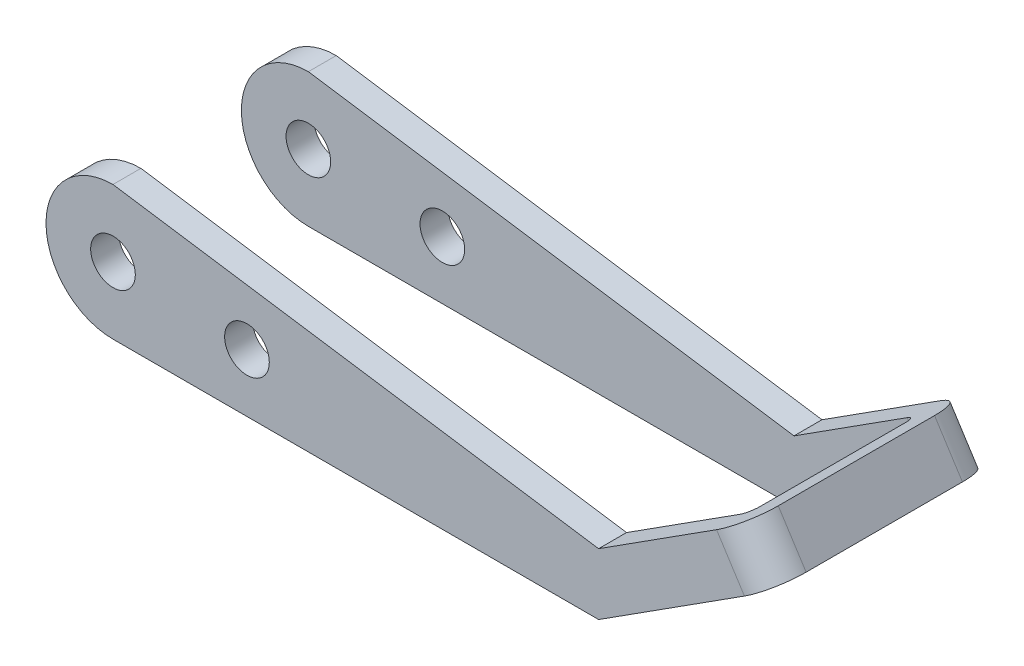
SolidWorks part; units mm, degrees
ref_plane "Piano frontale" through (0, 0, 0) normal (0, 0, 1) x (1, 0, 0)
ref_plane "Piano superiore" through (0, 0, 0) normal (0, 1, 0) x (1, 0, 0)
ref_plane "Piano destro" through (0, 0, 0) normal (1, 0, 0) x (0, 0, -1)
sketch "Schizzo1" plane through (0, 0, 0) normal (0, 0, 1) x (1, 0, 0)
  line L0 (0, -6) -> (43.5, -6)
  line L1 (0, 6) -> (43.5, -0.5011)
  line L2 (43.5, -6) -> (59.0854, 3.9673)
  line L3 (43.5, -0.5011) -> (56.5895, 7.87)
  line L4 (56.5895, 7.87) -> (59.0854, 3.9673)
  arc A0 (0, 6) -> (0, -6) centre (0, 0) ccw
  circle A1 centre (0, 0) radius 2
  circle A2 centre (12, -0.8) radius 2
  dimension "D1" = 12
  dimension "D6" = 4
  dimension "D7" = 4
  dimension "D2" = 43.5
  dimension "D3" = 8.5
  dimension "D4" = 18.5
  dimension "D5" = 32.6
  dimension "D8" = 0.8
  dimension "D9" = 12
extrude "Estrusione-Estrusione1" add sketch "Schizzo1" along normal blind 2.5
sketch "Schizzo3" plane through (0, 0, 0) normal (0, 0, -1) x (-1, 0, 0)
  line L0 (-56.5895, 7.87) -> (-59.0854, 3.9673)
  line L1 (-56.5895, 7.87) -> (-54.4834, 6.523)
  line L2 (-59.0854, 3.9673) -> (-56.9792, 2.6203)
  line L3 (-54.4834, 6.523) -> (-56.9792, 2.6203)
  dimension "D1" = 2.5
extrude "Estrusione-Estrusione2" add sketch "Schizzo3" along normal blind 7.5
sketch "Schizzo4" plane through (12.8544, -20.0998, 0) normal (-0.5388, 0.8425, 0) x (0.8425, 0.5388, 0)
  line L0 (51.9141, -2.5) -> (36.3767, -2.5) construction
  line L1 (51.9141, -2.5) -> (51.9141, 7.5) construction
  line L2 (51.9141, 0.5) -> (51.9141, -2.5)
  line L3 (51.9141, -2.5) -> (48.9141, -2.5)
  arc A1 (48.9141, -2.5) -> (51.9141, 0.5) centre (48.9141, 0.5) ccw
  dimension "D2" = 6
extrude "Taglio-Estrusione1" cut sketch "Schizzo4" against normal through all
sketch "Schizzo5" plane through (12.8544, -20.0998, 0) normal (-0.5388, 0.8425, 0) x (0.8425, 0.5388, 0)
  line L0 (49.4141, 7.5) -> (49.4141, 0) construction
  line L1 (49.4141, 0) -> (36.3767, 0) construction
  line L2 (49.4141, 1) -> (49.4141, 0)
  line L3 (49.4141, 0) -> (48.4141, 0)
  arc A0 (48.4141, 0) -> (49.4141, 1) centre (48.4141, 1) ccw
  dimension "D1" = 2
extrude "Estrusione-Estrusione3" add sketch "Schizzo5" against normal up to vertex (4.6325 mm away)
ref_plane "Piano3" through (0, 0, -7.5) normal (0, 0, 1) x (1, 0, 0)
mirror "Specchia4" about plane through (0, 0, -7.5) normal (0, 0, 1) of bodies 104
